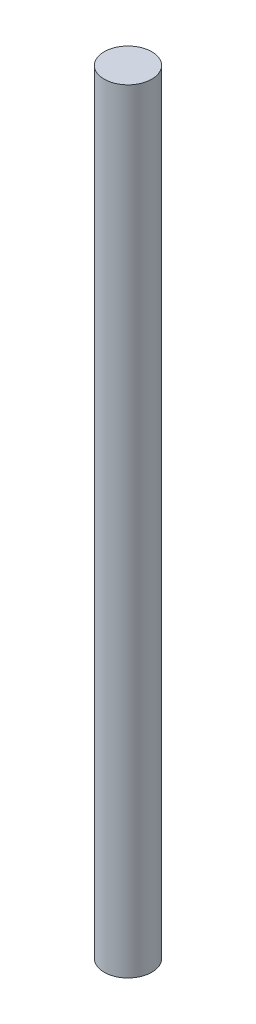
SolidWorks part; units mm, degrees
ref_plane "Front Plane" through (0, 0, 0) normal (0, 0, 1) x (1, 0, 0)
ref_plane "Top Plane" through (0, 0, 0) normal (0, 1, 0) x (1, 0, 0)
ref_plane "Right Plane" through (0, 0, 0) normal (1, 0, 0) x (0, 0, -1)
sketch "Sketch1" plane through (0, 0, 0) normal (0, 1, 0) x (1, 0, 0)
  circle A0 centre (0, 0) radius 4
  dimension "D1" = 8
extrude "Boss-Extrude1" add sketch "Sketch1" along normal blind 130
